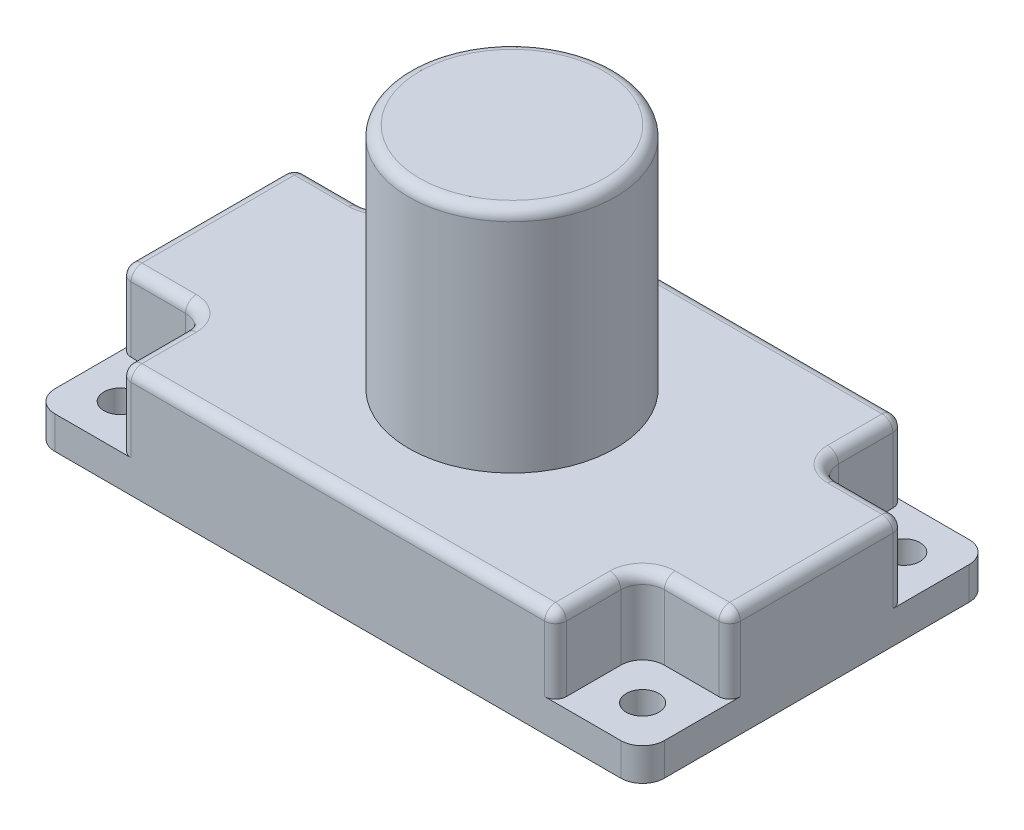
SolidWorks part; units mm, degrees
material "Caucho de silicio"
ref_plane "Alzado" through (0, 0, 0) normal (0, 0, 1) x (1, 0, 0)
ref_plane "Planta" through (0, 0, 0) normal (0, 1, 0) x (1, 0, 0)
ref_plane "Vista lateral" through (0, 0, 0) normal (1, 0, 0) x (0, 0, -1)
sketch "Croquis1" plane through (0, 0, 0) normal (0, 1, 0) x (1, 0, 0)
  line L1 (0, 0) -> (56, 0)
  line L2 (0, 0) -> (0, -32)
  line L3 (0, -32) -> (56, -32)
  line L4 (56, 0) -> (56, -32)
  dimension "D1" = 32
  dimension "D2" = 56
extrude "Saliente-Extruir1" add sketch "Croquis1" along normal blind 10
sketch "Croquis2" plane through (0, 10, 0) normal (0, 1, 0) x (1, 0, 0)
  line L0 (28, 0) -> (28, -32) construction
  line L1 (56, 0) -> (0, 0) construction
  line L2 (0, -32) -> (56, -32) construction
  line L3 (0, -16) -> (56, -16) construction
  line L4 (0, 0) -> (0, -32) construction
  line L5 (56, -32) -> (56, 0) construction
  circle A1 centre (28, -16) radius 9.5
  dimension "D1" = 19
extrude "Saliente-Extruir2" add sketch "Croquis2" along normal blind 21
sketch "Croquis3" plane through (0, 10, 0) normal (0, 1, 0) x (1, 0, 0)
  line L0 (0, -16) -> (56, -16) construction
  line L5 (48, -24) -> (56, -24)
  line L6 (48, -24) -> (48, -32)
  line L7 (48, -32) -> (56, -32)
  line L8 (56, -24) -> (56, -32)
  line L9 (0, 0) -> (0, -32) construction
  line L10 (56, 0) -> (0, 0) construction
  line L11 (56, -32) -> (56, 0) construction
  line L12 (28, 0) -> (28, -32) construction
  line L13 (0, -32) -> (56, -32) construction
  line L14 (48, 0) -> (56, 0)
  line L15 (56, -8) -> (56, 0)
  line L16 (48, -8) -> (56, -8)
  line L17 (48, -8) -> (48, 0)
  line L18 (8, -8) -> (8, 0)
  line L19 (8, -8) -> (0, -8)
  line L20 (0, -8) -> (0, 0)
  line L21 (8, 0) -> (0, 0)
  line L22 (8, -32) -> (0, -32)
  line L23 (0, -24) -> (0, -32)
  line L24 (8, -24) -> (0, -24)
  line L25 (8, -24) -> (8, -32)
  dimension "D1" = 8
  dimension "D2" = 48
  dimension "D3" = 24
extrude "Cortar-Extruir1" cut sketch "Croquis3" against normal blind 7
sketch "Croquis4" plane through (0, 3, 0) normal (0, 1, 0) x (1, 0, 0)
  line L0 (0, -24) -> (0, -32) construction
  line L1 (0, -32) -> (8, -32) construction
  line L3 (0, -8) -> (8, -8) construction
  line L4 (0, 0) -> (0, -8) construction
  line L5 (56, 0) -> (48, 0) construction
  line L6 (56, -8) -> (56, 0) construction
  line L7 (48, -32) -> (56, -32) construction
  line L8 (56, -32) -> (56, -24) construction
  circle A0 centre (4, -4) radius 1.5
  circle A1 centre (4, -28) radius 1.5
  circle A2 centre (52, -28) radius 1.5
  circle A3 centre (52, -4) radius 1.5
  dimension "D1" = 3
  dimension "D2" = 3
  dimension "D3" = 3
  dimension "D4" = 3
  dimension "D5" = 4
  dimension "D6" = 4
  dimension "D7" = 4
  dimension "D8" = 4
  dimension "D9" = 4
  dimension "D10" = 4
  dimension "D11" = 4
  dimension "D12" = 4
extrude "Cortar-Extruir2" cut sketch "Croquis4" against normal through all
fillet "Redondeo1" radius 2 8 edges at (48, 6.5, 8) (56, 1.5, 0) (56, 1.5, 32) (48, 6.5, 24) (8, 6.5, 8) (0, 1.5, 0) (0, 1.5, 32) (8, 6.5, 24)
fillet "Redondeo2" radius 1 4 edges at (0, 10, 16) (28, 10, 0) (56, 10, 16) (28, 10, 32)
fillet "Redondeo3" radius 1 28 edges at (8, 6, 0) (8, 9.7071, 0.2929) (8, 10, 3.5) (0, 6, 8) (0.2929, 9.7071, 8) (3.5, 10, 8) (48, 6, 0) (56, 6, 8) (55.7071, 9.7071, 8) (52.5, 10, 8) (48.5858, 10, 7.4142) (48, 10, 3.5) (56, 6, 24) (55.7071, 9.7071, 24) (52.5, 10, 24) (48.5858, 10, 24.5858) (48, 10, 28.5) (48, 6, 32) (8, 6, 32) (8, 9.7071, 31.7071) (8, 10, 28.5) (7.4142, 10, 24.5858) (3.5, 10, 24) (0, 6, 24) (7.4142, 10, 7.4142) (48, 9.7071, 0.2929) (48, 9.7071, 31.7071) (0.2929, 9.7071, 24)
fillet "Redondeo4" radius 1 1 edges at (28, 31, 25.5)
